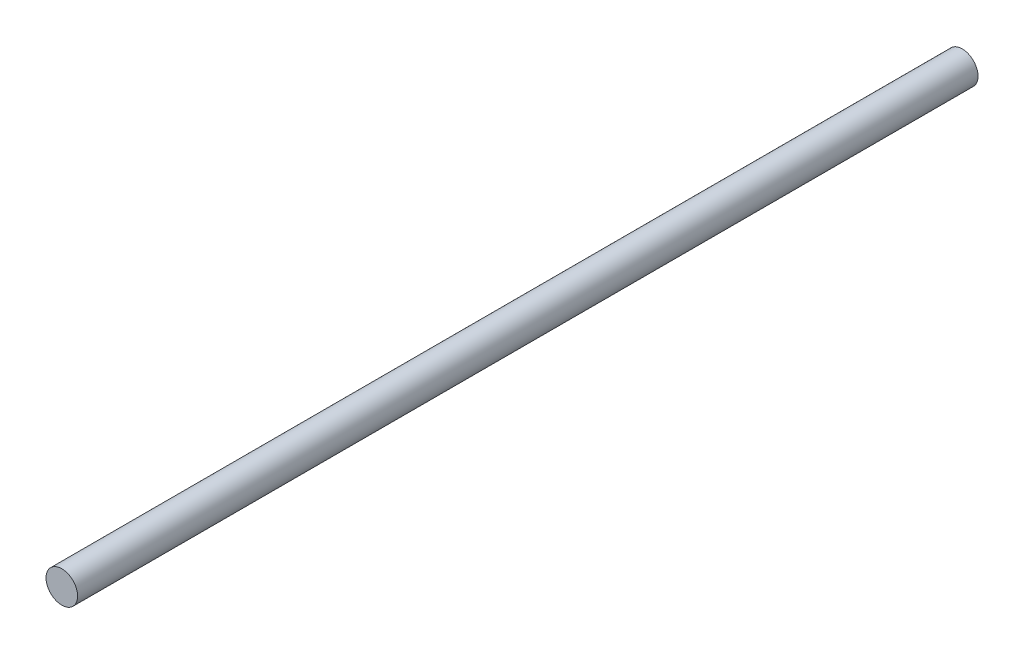
SolidWorks part; units mm, degrees
ref_plane "Front Plane" through (0, 0, 0) normal (0, 0, 1) x (1, 0, 0)
ref_plane "Top Plane" through (0, 0, 0) normal (0, 1, 0) x (1, 0, 0)
ref_plane "Right Plane" through (0, 0, 0) normal (1, 0, 0) x (0, 0, -1)
sketch "Sketch1" plane through (0, 0, 0) normal (0, 0, 1) x (1, 0, 0)
  circle A0 centre (0, 0) radius 4
  dimension "D1" = 8
extrude "Boss-Extrude1" add sketch "Sketch1" along normal blind 228
